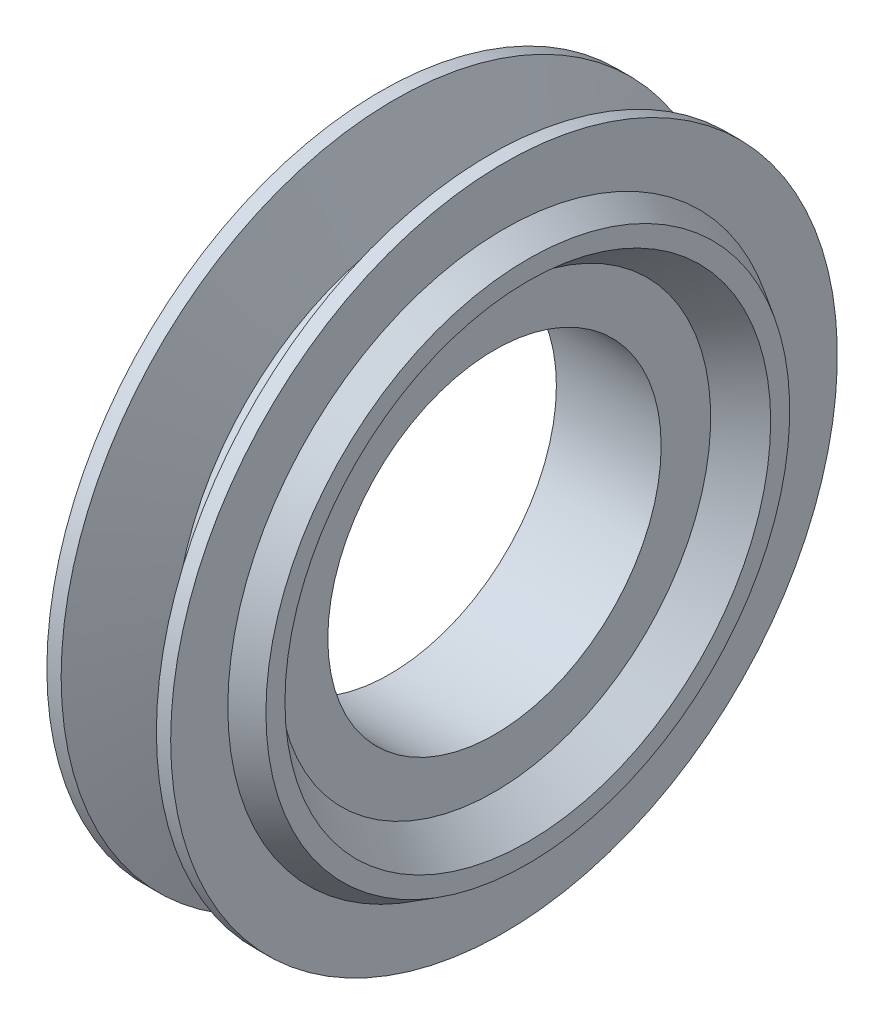
SolidWorks part; units mm, degrees
material "Обычная углеродистая сталь"
ref_plane "Спереди" through (0, 0, 0) normal (0, 0, 1) x (1, 0, 0)
ref_plane "Сверху" through (0, 0, 0) normal (0, 1, 0) x (1, 0, 0)
ref_plane "Справа" through (0, 0, 0) normal (1, 0, 0) x (0, 0, -1)
sketch "Эскиз1" plane through (0, 0, 0) normal (0, 0, 1) x (1, 0, 0)
  line L0 (-55.5492, 0) -> (55.5492, 0) construction
  line L1 (5.5, 0) -> (5.5, 22.7)
  line L2 (5.5, 22.7) -> (9, 25.5)
  line L3 (9, 25.5) -> (9, 27.5)
  line L4 (9, 27.5) -> (6.5, 29)
  line L5 (6.5, 29) -> (6.5, 35)
  line L6 (6.5, 35) -> (5, 35)
  line L7 (5, 35) -> (1, 22.7)
  line L8 (1, 22.7) -> (-1, 22.7)
  line L9 (-1, 22.7) -> (-5, 35)
  line L10 (-5, 35) -> (-6.5, 35)
  line L11 (-6.5, 35) -> (-6.5, 29)
  line L12 (-6.5, 29) -> (-9, 27.5)
  line L13 (-9, 27.5) -> (-9, 25.5)
  line L14 (-9, 25.5) -> (-5.5, 22.7)
  line L15 (-5.5, 22.7) -> (-5.5, 0)
  line L16 (0, 0) -> (0, 45.4) construction
  line L17 (-5.5, 0) -> (5.5, 0)
  point P21 (0, 22.7)
  dimension "D1" = 2
  dimension "D2" = 12.3
  dimension "D3" = 1.5
  dimension "D4" = 10
  dimension "D5" = 5
  dimension "D6" = 6
  dimension "D7" = 13
  dimension "D8" = 18
  dimension "D9" = 2
  dimension "D10" = 9.5
  dimension "D11" = 35
  dimension "D12" = 9
  dimension "D13" = 11
  dimension "D14" = 5.5
revolve "Повернуть1" add sketch "Эскиз1" angle 360 about L0
sketch "Эскиз2" plane through (5.5, 0, 0) normal (1, 0, 0) x (0, 0, -1)
  circle A0 centre (0, 0) radius 17.5
  dimension "D1" = 35
extrude "Вырез-Вытянуть1" cut sketch "Эскиз2" against normal through all
sketch "Эскиз4" plane through (0, 0, 0) normal (0, 0, 1) x (1, 0, 0)
  line L0 (0, 0) -> (0, 45.4) construction
  line L1 (-2.8374, 26) -> (2.8374, 26)
  line L2 (-2.8374, 26) -> (-2.8374, 21.1262)
  line L3 (-2.8374, 21.1262) -> (2.8374, 21.1262)
  line L4 (2.8374, 26) -> (2.8374, 21.1262)
  line L5 (-2.8374, 26) -> (2.8374, 21.1262) construction
  line L6 (-2.8374, 21.1262) -> (2.8374, 26) construction
  line L7 (6.5, 35) -> (5, 35) construction
  point P0 (0, 23.5631)
  dimension "D1" = 9
revolve "Повернуть2" add sketch "Эскиз4" angle 360 about L0
ref_plane "Плоскость1" through (0, 0, 0) normal (-1, 0, 0) x (0, 0, 1)
